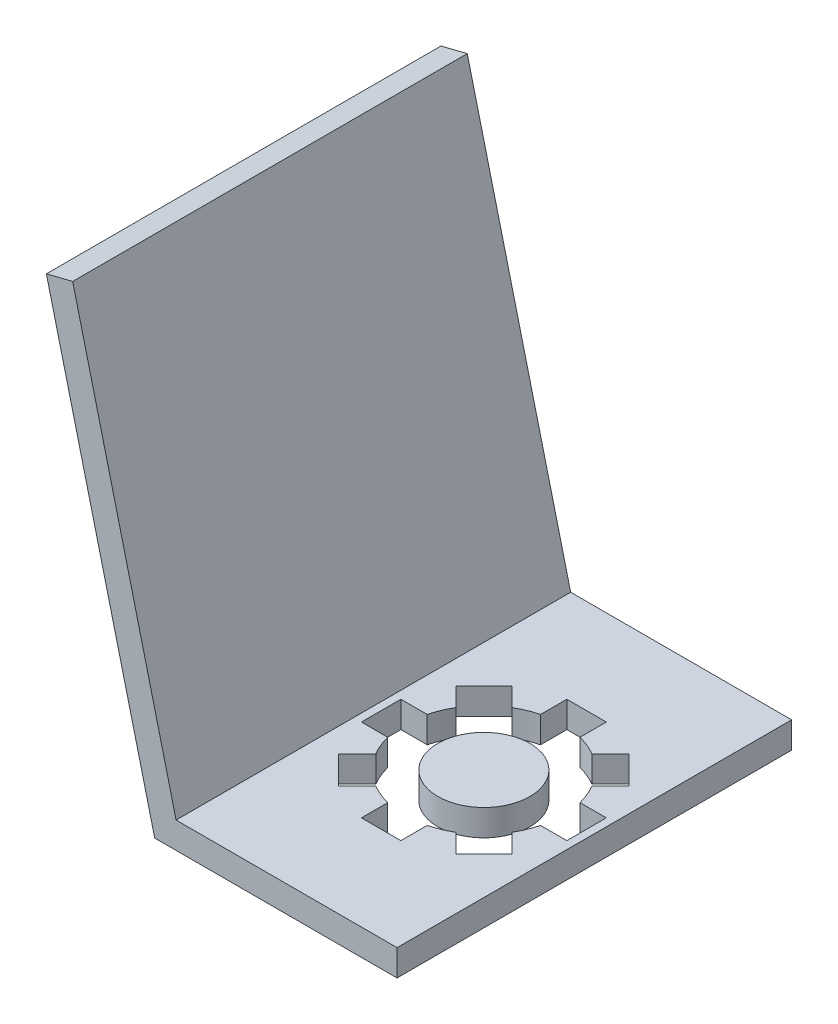
SolidWorks part; units mm, degrees
ref_plane "Front Plane" through (0, 0, 0) normal (0, 0, 1) x (1, 0, 0)
ref_plane "Top Plane" through (0, 0, 0) normal (0, 1, 0) x (1, 0, 0)
ref_plane "Right Plane" through (0, 0, 0) normal (1, 0, 0) x (0, 0, -1)
sketch "Sketch1" plane through (0, 0, 0) normal (0, 0, 1) x (1, 0, 0)
  line L0 (0, 0) -> (426.72, 0)
  line L1 (0, 0) -> (-199.7065, 800.9791)
  line L2 (-199.7065, 800.9791) -> (-250.5065, 788.3133)
  line L3 (426.72, 0) -> (426.72, -50.8)
  line L4 (-250.5065, 788.3133) -> (-41.2921, -50.8)
  line L5 (-41.2921, -50.8) -> (426.72, -50.8)
  dimension "D1" = 426.72
  dimension "D2" = 825.5
  dimension "D3" = 104
  dimension "D4" = 50.8
  dimension "D5" = 50.8
extrude "Boss-Extrude1" add sketch "Sketch1" along normal blind 762 contours L5 L3 L0 L1 L2 L4
sketch "Sketch2" plane through (0, 0, 0) normal (0, 1, 0) x (1, 0, 0)
  line L0 (213.36, 0) -> (213.36, -182.6393) construction
  line L1 (0, 0) -> (426.72, 0) construction
  line L2 (0, -762) -> (426.72, -762) construction
  line L3 (213.36, -292.1) -> (213.36, -762) construction
  line L4 (175.26, -182.6393) -> (251.46, -182.6393)
  line L5 (175.26, -182.6393) -> (175.26, -233.4393)
  line L7 (251.46, -182.6393) -> (251.46, -233.4393)
  line L8 (326.6814, -213.7971) -> (290.7604, -249.7181)
  line L9 (326.6814, -213.7971) -> (380.5629, -267.6786)
  line L10 (380.5629, -267.6786) -> (344.6419, -303.5996)
  line L11 (411.7207, -342.9) -> (360.9207, -342.9)
  line L12 (411.7207, -342.9) -> (411.7207, -419.1)
  line L13 (411.7207, -419.1) -> (360.9207, -419.1)
  line L14 (380.5629, -494.3214) -> (344.6419, -458.4004)
  line L15 (380.5629, -494.3214) -> (326.6814, -548.2029)
  line L16 (326.6814, -548.2029) -> (290.7604, -512.2819)
  line L17 (251.46, -579.3607) -> (251.46, -528.5607)
  line L18 (251.46, -579.3607) -> (175.26, -579.3607)
  line L19 (175.26, -579.3607) -> (175.26, -528.5607)
  line L20 (100.0386, -548.2029) -> (135.9596, -512.2819)
  line L21 (100.0386, -548.2029) -> (46.1571, -494.3214)
  line L22 (46.1571, -494.3214) -> (82.0781, -458.4004)
  line L23 (14.9993, -419.1) -> (65.7993, -419.1)
  line L24 (14.9993, -419.1) -> (14.9993, -342.9)
  line L25 (14.9993, -342.9) -> (65.7993, -342.9)
  line L26 (46.1571, -267.6786) -> (82.0781, -303.5996)
  line L27 (46.1571, -267.6786) -> (100.0386, -213.7971)
  line L28 (100.0386, -213.7971) -> (135.9596, -249.7181)
  arc A0 (175.26, -233.4393) -> (135.9596, -249.7181) centre (213.36, -381) ccw
  circle A1 centre (213.36, -381) radius 88.9
  arc A2 (290.7604, -249.7181) -> (251.46, -233.4393) centre (213.36, -381) ccw
  arc A3 (82.0781, -303.5996) -> (65.7993, -342.9) centre (213.36, -381) ccw
  arc A4 (360.9207, -342.9) -> (344.6419, -303.5996) centre (213.36, -381) ccw
  arc A5 (344.6419, -458.4004) -> (360.9207, -419.1) centre (213.36, -381) ccw
  arc A6 (251.46, -528.5607) -> (290.7604, -512.2819) centre (213.36, -381) ccw
  arc A7 (135.9596, -512.2819) -> (175.26, -528.5607) centre (213.36, -381) ccw
  arc A8 (65.7993, -419.1) -> (82.0781, -458.4004) centre (213.36, -381) ccw
  point P9 (213.36, -208.0393)
  point P46 (213.36, -381)
  dimension "D1" = 304.8
  dimension "D2" = 177.8
  dimension "D3" = 50.8
  dimension "D4" = 76.2
  dimension "D5" = 8
extrude "Cut-Extrude1" cut sketch "Sketch2" against normal blind 1016
